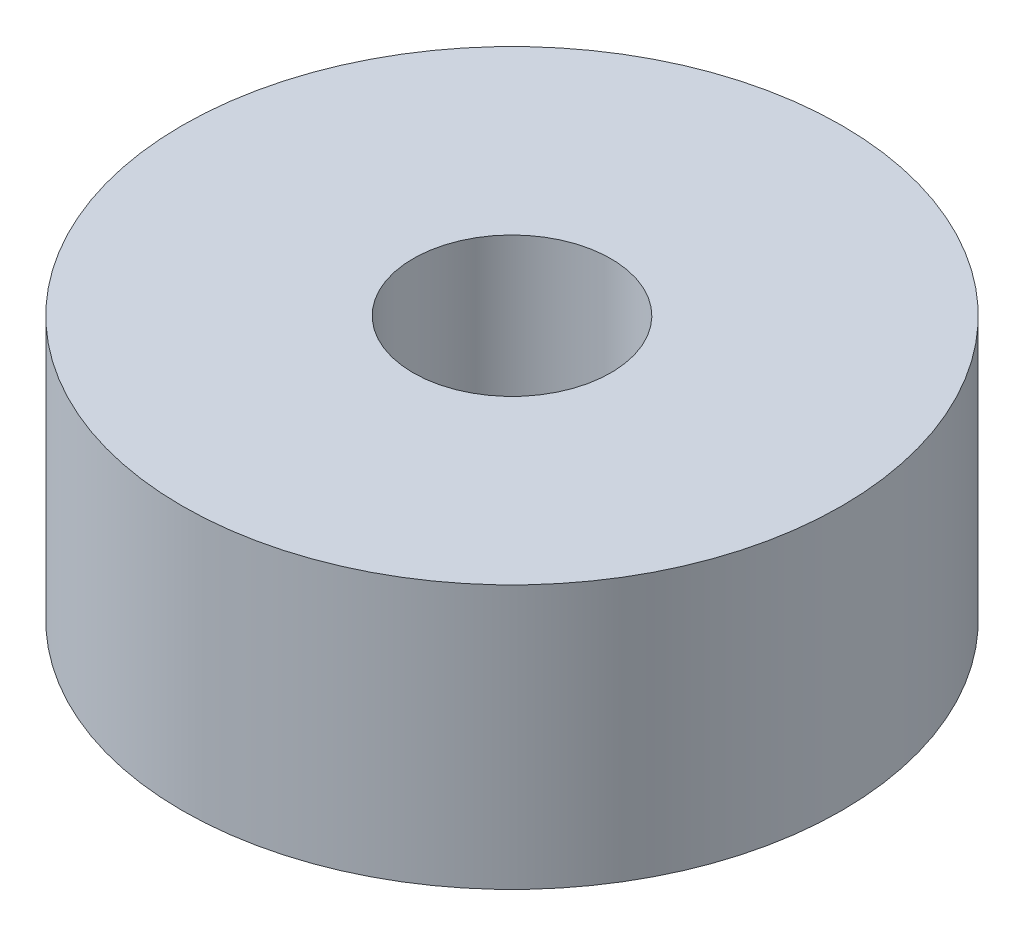
SolidWorks part; units mm, degrees
ref_plane "Front Plane" through (0, 0, 0) normal (0, 0, 1) x (1, 0, 0)
ref_plane "Top Plane" through (0, 0, 0) normal (0, 1, 0) x (1, 0, 0)
ref_plane "Right Plane" through (0, 0, 0) normal (1, 0, 0) x (0, 0, -1)
sketch "Sketch1" plane through (0, 0, 0) normal (0, 1, 0) x (1, 0, 0)
  circle A0 centre (0, 0) radius 5
  circle A1 centre (0, 0) radius 1.5
  dimension "D1" = 10
  dimension "D2" = 3
extrude "Boss-Extrude1" add sketch "Sketch1" along normal blind 4
